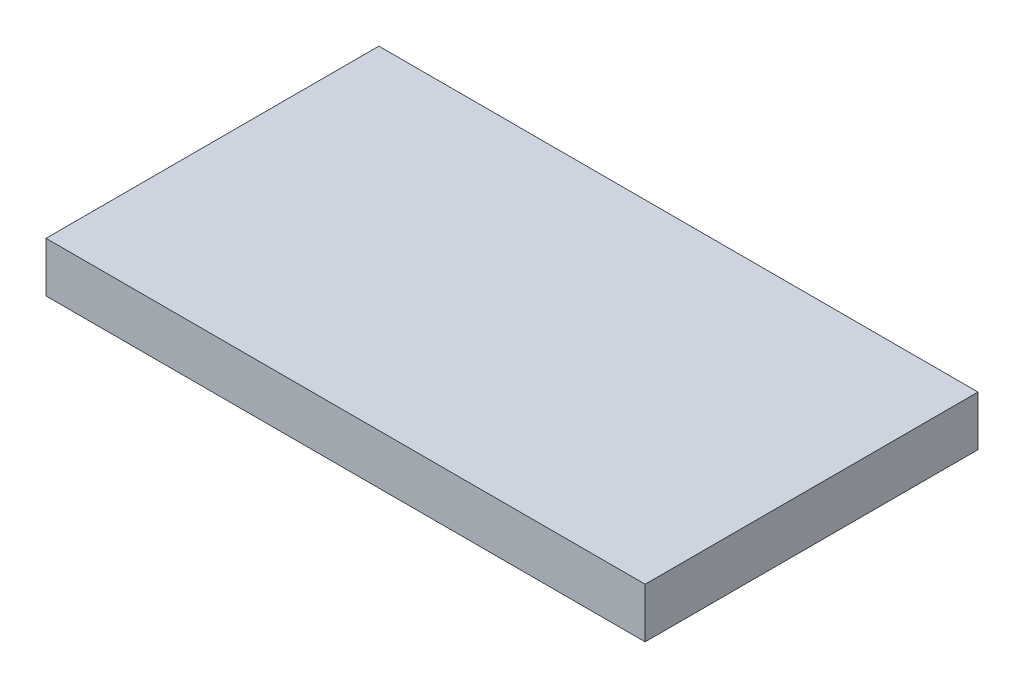
SolidWorks part; units mm, degrees
ref_plane "前视基准面" through (0, 0, 0) normal (0, 0, 1) x (1, 0, 0)
ref_plane "上视基准面" through (0, 0, 0) normal (0, 1, 0) x (1, 0, 0)
ref_plane "右视基准面" through (0, 0, 0) normal (1, 0, 0) x (0, 0, -1)
sketch "草图1" plane through (0, 0, 0) normal (0, 0, 1) x (1, 0, 0)
  line L1 (-349.5457, -3.9719) -> (10.4543, -3.9719)
  line L2 (-349.5457, 4.0281) -> (-349.5457, 26.0281)
  line L3 (-349.5457, 26.0281) -> (10.4543, 26.0281)
  line L4 (10.4543, 4.0281) -> (10.4543, 26.0281)
  line L14 (10.4543, -3.9719) -> (10.4543, 4.0281)
  line L15 (-349.5457, -3.9719) -> (-349.5457, 4.0281)
  dimension "D1" = 30
  dimension "D2" = 360
extrude "凸台-拉伸1" add sketch "草图1" along normal blind 200
